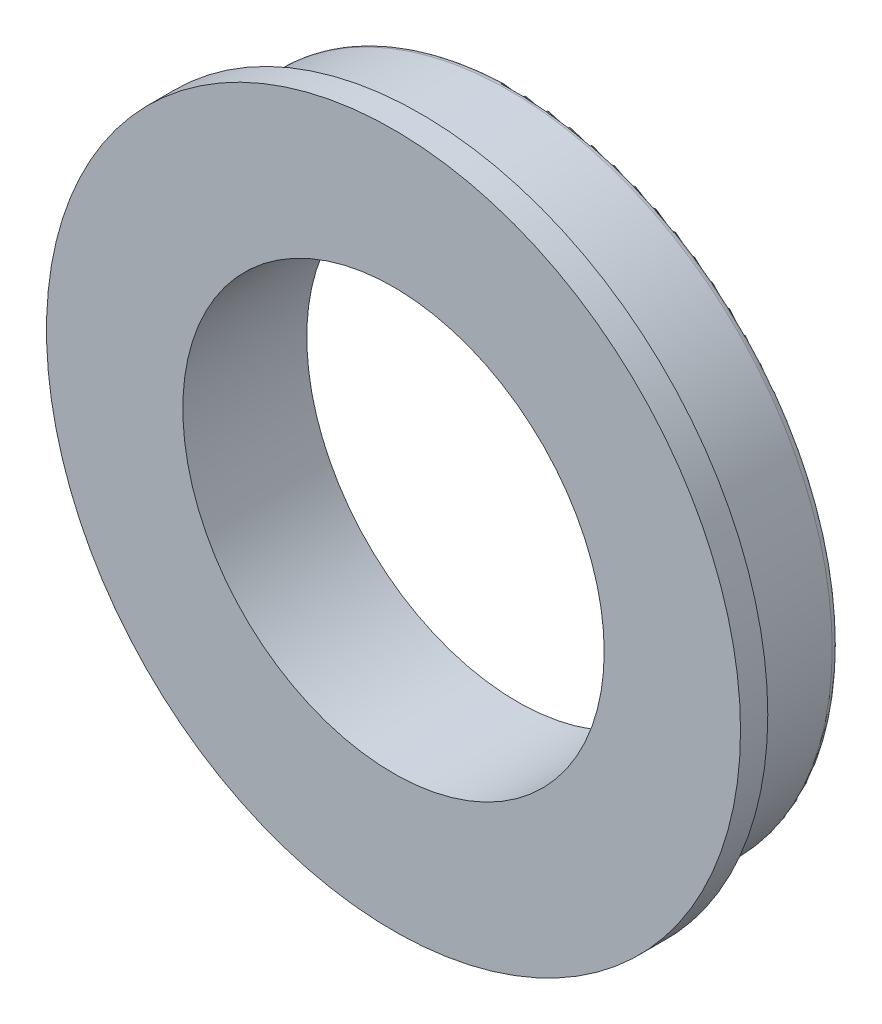
SolidWorks part; units mm, degrees
material "1.5714 (16NiCr4)"
ref_plane "前视基准面" through (0, 0, 0) normal (0, 0, 1) x (1, 0, 0)
ref_plane "上视基准面" through (0, 0, 0) normal (0, 1, 0) x (1, 0, 0)
ref_plane "右视基准面" through (0, 0, 0) normal (1, 0, 0) x (0, 0, -1)
sketch "草图1" plane through (0, 0, 0) normal (0, 0, 1) x (1, 0, 0)
  circle A0 centre (0, 0) radius 8.5
  circle A1 centre (0, 0) radius 13
extrude "凸台-拉伸1" add sketch "草图1" along normal blind 5
sketch "草图2" plane through (0, 0, 5) normal (0, 0, 1) x (1, 0, 0)
  circle A0 centre (0, 0) radius 14
  circle A1 centre (0, 0) radius 13
extrude "凸台-拉伸2" add sketch "草图2" against normal blind 1.1
fillet "圆角1" radius 0.3 1 edges at (13, 0, 0)
